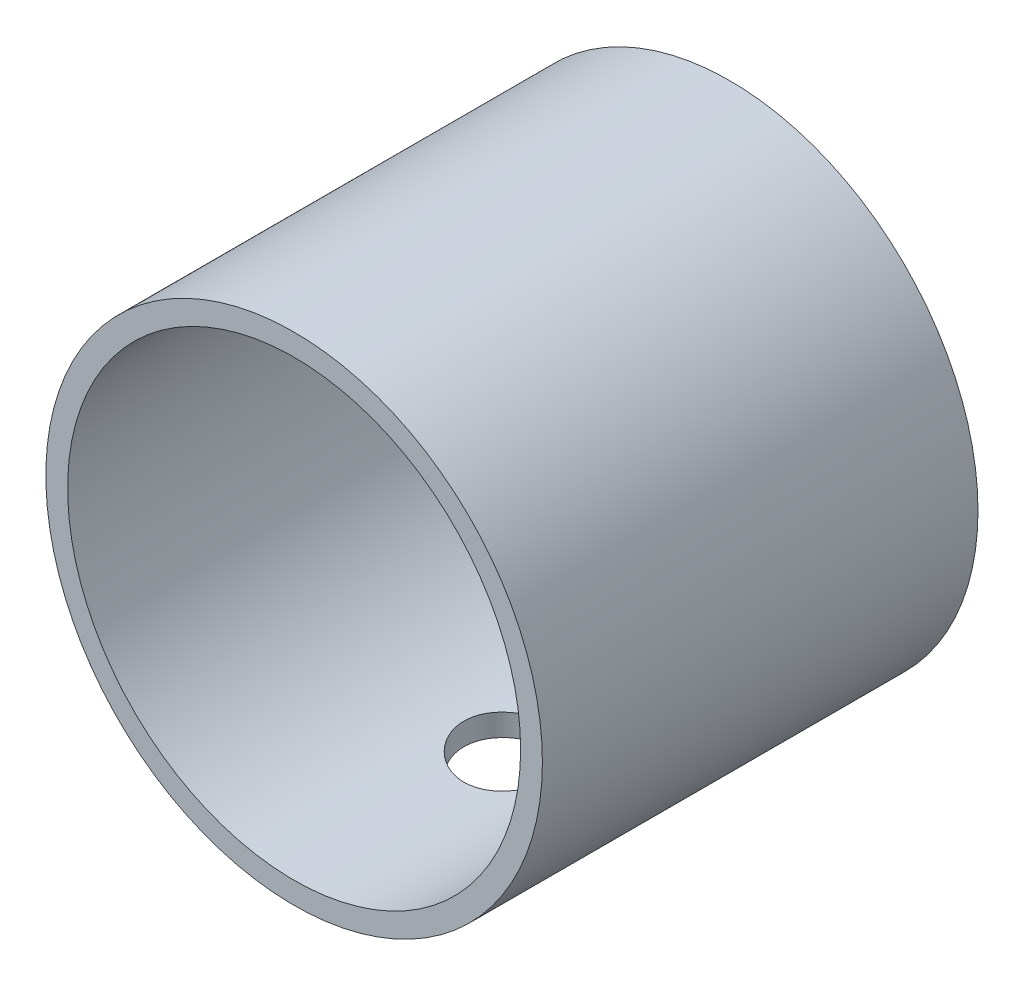
SolidWorks part; units mm, degrees
material "ASTM A36 Steel"
ref_plane "Front Plane" through (0, 0, 0) normal (0, 0, 1) x (1, 0, 0)
ref_plane "Top Plane" through (0, 0, 0) normal (0, 1, 0) x (1, 0, 0)
ref_plane "Right Plane" through (0, 0, 0) normal (1, 0, 0) x (0, 0, -1)
sketch "Sketch1" plane through (0, 0, 0) normal (0, 0, 1) x (1, 0, 0)
  circle A0 centre (0, 0) radius 28.5
  circle A1 centre (0, 0) radius 26
  dimension "D1" = 57
  dimension "D2" = 52
extrude "Boss-Extrude1" add sketch "Sketch1" along normal blind 50
sketch "Sketch2" plane through (0, 0, 0) normal (0, 1, 0) x (1, 0, 0)
  circle A0 centre (0, -25) radius 5.5
  dimension "D1" = 11
extrude "Cut-Extrude1" cut sketch "Sketch2" against normal blind 50
